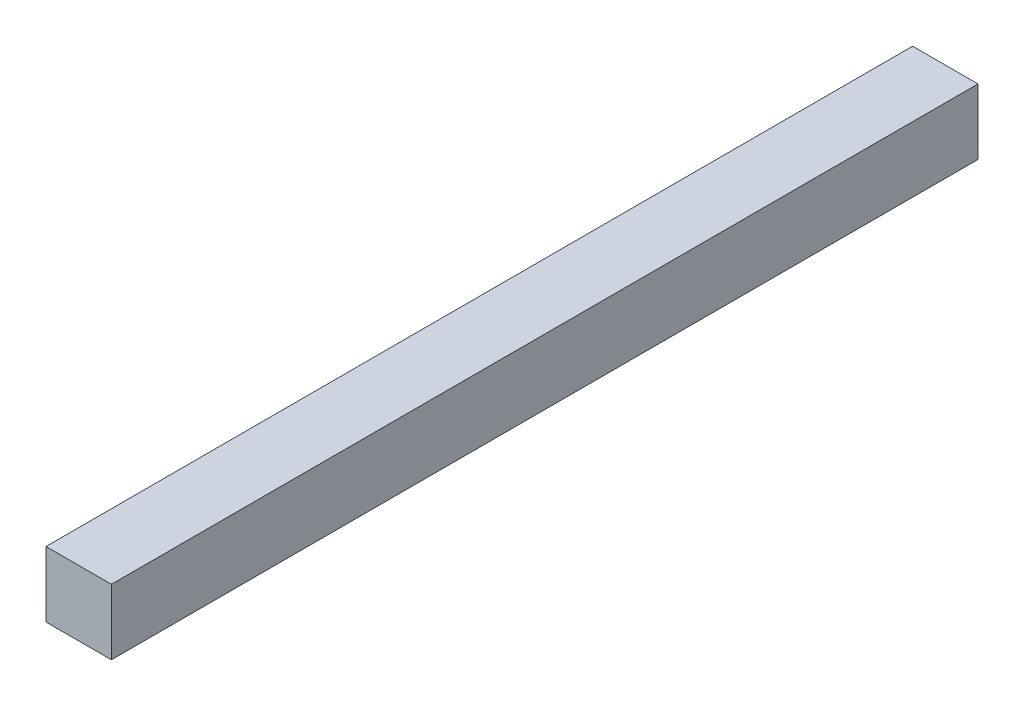
SolidWorks part; units mm, degrees
ref_plane "Front Plane" through (0, 0, 0) normal (0, 0, 1) x (1, 0, 0)
ref_plane "Top Plane" through (0, 0, 0) normal (0, 1, 0) x (1, 0, 0)
ref_plane "Right Plane" through (0, 0, 0) normal (1, 0, 0) x (0, 0, -1)
sketch "Sketch1" plane through (0, 0, 0) normal (0, 0, 1) x (1, 0, 0)
  line L1 (-10, -10) -> (10, -10)
  line L2 (-10, -10) -> (-10, 10)
  line L3 (-10, 10) -> (10, 10)
  line L4 (10, -10) -> (10, 10)
  line L5 (-10, -10) -> (10, 10) construction
  line L6 (-10, 10) -> (10, -10) construction
  point P0 (0, 0)
  dimension "D1" = 20
extrude "Boss-Extrude1" add sketch "Sketch1" along normal blind 265
